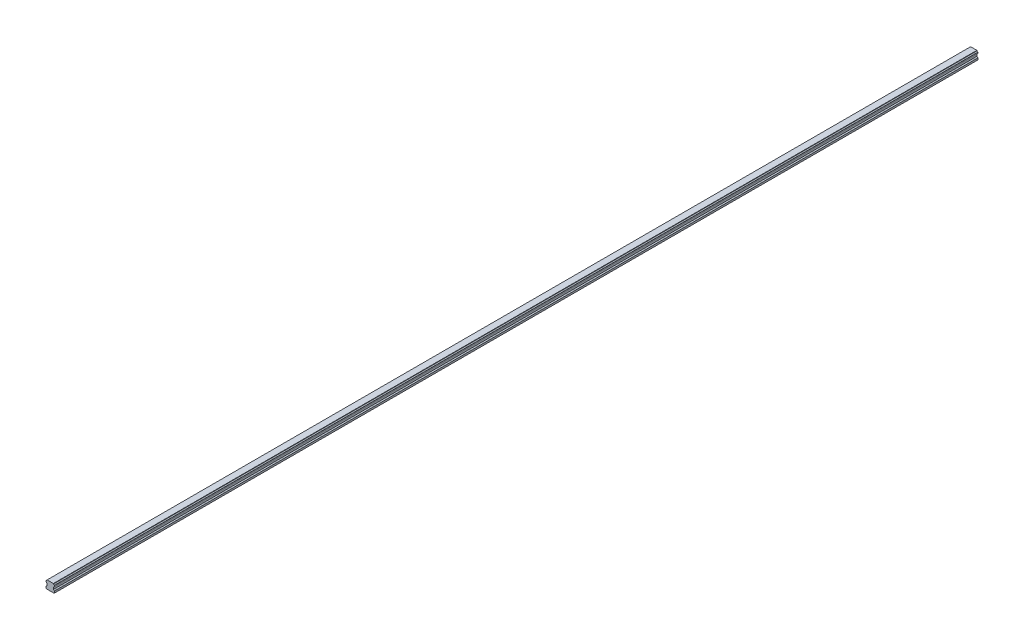
SolidWorks part; units mm, degrees
material "Простая углеродистая сталь"
ref_plane "Спереди" through (0, 0, 0) normal (0, 0, 1) x (1, 0, 0)
ref_plane "Сверху" through (0, 0, 0) normal (0, 1, 0) x (1, 0, 0)
ref_plane "Справа" through (0, 0, 0) normal (1, 0, 0) x (0, 0, -1)
sketch "Model" plane through (0, 0, 0) normal (0, 0, 1) x (1, 0, 0)
  line L0 (-11.5, -10) -> (-10.5, -11)
  line L1 (-10.5, -11) -> (10.5, -11)
  line L2 (10.5, -11) -> (11.5, -10)
  line L3 (11.5, -10) -> (11.5, -5)
  line L4 (11.5, -5) -> (8.5, -3)
  line L5 (8.5, -3) -> (8.5, 2)
  line L6 (8.5, 2) -> (9.0076, 2.5076)
  line L7 (11.3054, 4.8054) -> (11.5, 5)
  line L8 (11.5, 5) -> (11.5, 8)
  line L9 (11.5, 8) -> (11.3054, 8.1946)
  line L10 (9.0076, 10.4924) -> (8.5, 11)
  line L11 (8.5, 11) -> (-8.5, 11)
  line L12 (-8.5, 11) -> (-9.0076, 10.4924)
  line L13 (-11.3054, 8.1946) -> (-11.5, 8)
  line L14 (-11.5, 8) -> (-11.5, 5)
  line L15 (-11.5, 5) -> (-11.3054, 4.8054)
  line L16 (-9.0076, 2.5076) -> (-8.5, 2)
  line L17 (-8.5, 2) -> (-8.5, -3)
  line L18 (-8.5, -3) -> (-11.5, -5)
  line L19 (-11.5, -5) -> (-11.5, -10)
  arc A0 (11.3054, 4.8054) -> (9.0076, 2.5076) centre (11.5, 2.313) ccw
  arc A1 (9.0076, 10.4924) -> (11.3054, 8.1946) centre (11.5, 10.687) ccw
  arc A2 (-11.3054, 8.1946) -> (-9.0076, 10.4924) centre (-11.5, 10.687) ccw
  arc A3 (-9.0076, 2.5076) -> (-11.3054, 4.8054) centre (-11.5, 2.313) ccw
extrude "Бобышка-Вытянуть1" add sketch "Model" against normal blind 2500
